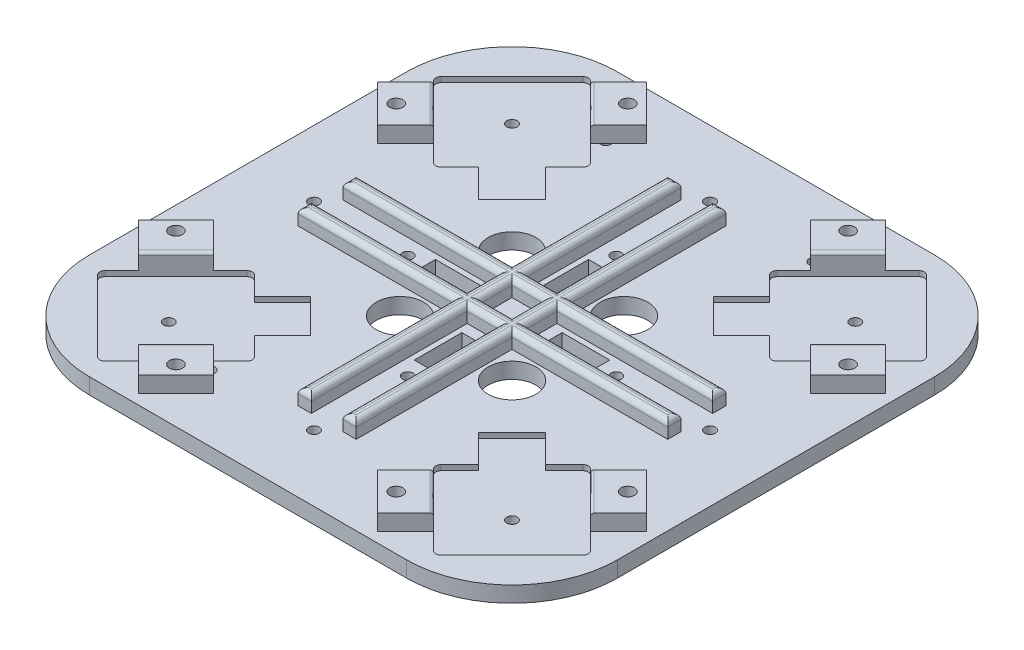
SolidWorks part; units mm, degrees
ref_plane "Спереди" through (0, 0, 0) normal (0, 0, 1) x (1, 0, 0)
ref_plane "Сверху" through (0, 0, 0) normal (0, 1, 0) x (1, 0, 0)
ref_plane "Справа" through (0, 0, 0) normal (1, 0, 0) x (0, 0, -1)
sketch "Эскиз1" plane through (0, 0, 0) normal (0, 1, 0) x (1, 0, 0)
  line L1 (-100, -100) -> (100, -100)
  line L2 (-100, -100) -> (-100, 100)
  line L3 (-100, 100) -> (100, 100)
  line L4 (100, -100) -> (100, 100)
  line L5 (0, 100) -> (0, -100) construction
  line L6 (-100, 0) -> (100, 0) construction
  line L7 (-39.5, -75) -> (39.5, -75) construction
  line L8 (-39.5, -75) -> (-39.5, 75) construction
  line L9 (-39.5, 75) -> (39.5, 75) construction
  line L10 (39.5, -75) -> (39.5, 75) construction
  line L11 (0, 75) -> (0, -75) construction
  line L12 (-39.5, 0) -> (39.5, 0) construction
  line L13 (-65, -65) -> (65, -65) construction
  line L14 (-65, -65) -> (-65, 65) construction
  line L15 (-65, 65) -> (65, 65) construction
  line L16 (65, -65) -> (65, 65) construction
  line L17 (0, 65) -> (0, -65) construction
  line L18 (-65, 0) -> (65, 0) construction
  circle A0 centre (-39.5, 75) radius 2
  circle A1 centre (39.5, 75) radius 2
  circle A2 centre (39.5, -75) radius 2
  circle A3 centre (-39.5, -75) radius 2
  circle A4 centre (39.5, 0) radius 2
  circle A5 centre (-39.5, 0) radius 2
  circle A6 centre (0, 39.5) radius 2
  circle A7 centre (0, -39.5) radius 2
  circle A8 centre (-75, 0) radius 2
  circle A9 centre (0, 75) radius 2
  circle A10 centre (75, 0) radius 2
  circle A11 centre (0, -75) radius 2
  circle A12 centre (-65, 65) radius 2
  circle A13 centre (65, 65) radius 2
  circle A14 centre (65, -65) radius 2
  circle A15 centre (-65, -65) radius 2
  point P0 (0, 0)
  point P4 (0, 0)
  point P11 (0, 0)
  point P27 (0, 0)
  dimension "D4" = 4
  dimension "D5" = 79
  dimension "D6" = 75
  dimension "D1" = 200
  dimension "D2" = 79
  dimension "D3" = 150
  dimension "D8" = 130
  dimension "D7" = 4
extrude "Бобышка-Вытянуть1" add sketch "Эскиз1" along normal blind 6
sketch "Эскиз2" plane through (0, 6, 0) normal (0, 1, 0) x (1, 0, 0)
  line L0 (0, 72.2532) -> (0, 0) construction
  line L1 (0, 0) -> (100, 100) construction
  line L2 (63.6396, 33.9411) -> (33.9411, 63.6396)
  line L3 (63.6396, 33.9411) -> (93.3381, 63.6396)
  line L4 (33.9411, 63.6396) -> (63.6396, 93.3381)
  line L5 (93.3381, 63.6396) -> (63.6396, 93.3381)
  line L6 (63.6396, 33.9411) -> (63.6396, 93.3381) construction
  line L7 (33.9411, 63.6396) -> (93.3381, 63.6396) construction
  line L8 (33.9411, -63.6396) -> (63.6396, -33.9411)
  line L9 (33.9411, -63.6396) -> (63.6396, -93.3381)
  line L10 (63.6396, -93.3381) -> (93.3381, -63.6396)
  line L11 (63.6396, -33.9411) -> (93.3381, -63.6396)
  line L12 (-63.6396, -33.9411) -> (-33.9411, -63.6396)
  line L13 (-63.6396, -33.9411) -> (-93.3381, -63.6396)
  line L14 (-93.3381, -63.6396) -> (-63.6396, -93.3381)
  line L15 (-33.9411, -63.6396) -> (-63.6396, -93.3381)
  line L16 (-33.9411, 63.6396) -> (-63.6396, 33.9411)
  line L17 (-33.9411, 63.6396) -> (-63.6396, 93.3381)
  line L18 (-63.6396, 93.3381) -> (-93.3381, 63.6396)
  line L19 (-63.6396, 33.9411) -> (-93.3381, 63.6396)
  point P6 (63.6396, 63.6396)
  point P24 (0, 0)
  dimension "D1" = 42
  dimension "D2" = 90
  dimension "D3" = 4
extrude "Вырез-Вытянуть1" cut sketch "Эскиз2" against normal blind 2
fillet "Скругление1" radius 2 16 edges at (63.6396, 5, -33.9411) (33.9411, 5, -63.6396) (93.3381, 5, -63.6396) (63.6396, 5, -93.3381) (-63.6396, 5, -93.3381) (-63.6396, 5, -33.9411) (-93.3381, 5, -63.6396) (-33.9411, 5, -63.6396) (63.6396, 5, 93.3381) (93.3381, 5, 63.6396) (63.6396, 5, 33.9411) (33.9411, 5, 63.6396) (-63.6396, 5, 93.3381) (-33.9411, 5, 63.6396) (-63.6396, 5, 33.9411) (-93.3381, 5, 63.6396)
sketch "Эскиз3" plane through (0, 6, 0) normal (0, 1, 0) x (1, 0, 0)
  line L0 (48.7904, 48.7904) -> (67.3817, 67.3817) construction
  line L1 (35.3553, 62.2254) -> (62.2254, 35.3553) construction
  line L2 (48.7904, 78.4889) -> (78.4889, 48.7904) construction
  line L3 (62.2254, 91.9239) -> (35.3553, 65.0538) construction
  line L4 (65.0538, 35.3553) -> (91.9239, 62.2254) construction
  line L5 (41.7193, 71.4178) -> (55.8614, 85.5599)
  line L6 (41.7193, 71.4178) -> (31.1127, 82.0244)
  line L7 (55.8614, 85.5599) -> (45.2548, 96.1665)
  line L8 (31.1127, 82.0244) -> (45.2548, 96.1665)
  line L9 (62.2254, 91.9239) -> (35.3553, 65.0538) construction
  line L10 (85.5599, 55.8614) -> (96.1665, 45.2548)
  line L11 (82.0244, 31.1127) -> (96.1665, 45.2548)
  line L12 (71.4178, 41.7193) -> (82.0244, 31.1127)
  line L13 (71.4178, 41.7193) -> (85.5599, 55.8614)
  line L44 (65.0538, 35.3553) -> (91.9239, 62.2254) construction
  line L45 (0, 128.3294) -> (0, 0) construction
  line L64 (0, 0) -> (145.1139, 0) construction
  line L65 (62.2254, 91.9239) -> (35.3553, 65.0538) construction
  line L90 (48.7904, -78.4889) -> (78.4889, -48.7904) construction
  line L91 (48.7904, -48.7904) -> (67.3817, -67.3817) construction
  line L92 (71.4178, -41.7193) -> (85.5599, -55.8614)
  line L93 (71.4178, -41.7193) -> (82.0244, -31.1127)
  line L94 (82.0244, -31.1127) -> (96.1665, -45.2548)
  line L95 (85.5599, -55.8614) -> (96.1665, -45.2548)
  line L96 (31.1127, -82.0244) -> (45.2548, -96.1665)
  line L97 (55.8614, -85.5599) -> (45.2548, -96.1665)
  line L98 (41.7193, -71.4178) -> (31.1127, -82.0244)
  line L99 (41.7193, -71.4178) -> (55.8614, -85.5599)
  line L100 (-48.7904, -48.7904) -> (-67.3817, -67.3817) construction
  line L101 (-48.7904, -78.4889) -> (-78.4889, -48.7904) construction
  line L102 (-48.7904, 78.4889) -> (-78.4889, 48.7904) construction
  line L103 (-48.7904, 48.7904) -> (-67.3817, 67.3817) construction
  line L104 (-41.7193, -71.4178) -> (-55.8614, -85.5599)
  line L105 (-41.7193, -71.4178) -> (-31.1127, -82.0244)
  line L106 (-55.8614, -85.5599) -> (-45.2548, -96.1665)
  line L107 (-31.1127, -82.0244) -> (-45.2548, -96.1665)
  line L108 (-85.5599, -55.8614) -> (-96.1665, -45.2548)
  line L109 (-82.0244, -31.1127) -> (-96.1665, -45.2548)
  line L110 (-71.4178, -41.7193) -> (-82.0244, -31.1127)
  line L111 (-71.4178, -41.7193) -> (-85.5599, -55.8614)
  line L112 (-71.4178, 41.7193) -> (-85.5599, 55.8614)
  line L113 (-71.4178, 41.7193) -> (-82.0244, 31.1127)
  line L114 (-82.0244, 31.1127) -> (-96.1665, 45.2548)
  line L115 (-85.5599, 55.8614) -> (-96.1665, 45.2548)
  line L116 (-31.1127, 82.0244) -> (-45.2548, 96.1665)
  line L117 (-55.8614, 85.5599) -> (-45.2548, 96.1665)
  line L118 (-41.7193, 71.4178) -> (-31.1127, 82.0244)
  line L119 (-41.7193, 71.4178) -> (-55.8614, 85.5599)
  point P16 (48.7904, 78.4889)
  dimension "D1" = 20
  dimension "D2" = 15
extrude "Бобышка-Вытянуть3" add sketch "Эскиз3" along normal blind 6
fillet "Скругление4" radius 40 4 edges at (100, 3, -100) (100, 3, 100) (-100, 3, 100) (-100, 3, -100)
sketch "Эскиз4" plane through (0, 12, 0) normal (0, 1, 0) x (1, 0, 0)
  line L0 (89.0955, 38.1838) -> (38.1838, 89.0955) construction
  line L1 (82.0244, 31.1127) -> (96.1665, 45.2548) construction
  line L2 (45.2548, 96.1665) -> (31.1127, 82.0244) construction
  line L3 (41.7193, 71.4178) -> (55.8614, 85.5599) construction
  line L4 (48.7904, 48.7904) -> (78.4889, 78.4889) construction
  line L5 (35.3553, 62.2254) -> (62.2254, 35.3553) construction
  line L6 (91.9239, 65.0538) -> (65.0538, 91.9239) construction
  line L7 (0, 119.2498) -> (0, 0) construction
  line L8 (0, 0) -> (156.895, 0) construction
  line L9 (48.7904, -48.7904) -> (78.4889, -78.4889) construction
  line L10 (89.0955, -38.1838) -> (38.1838, -89.0955) construction
  line L11 (-89.0955, -38.1838) -> (-38.1838, -89.0955) construction
  line L12 (-48.7904, -48.7904) -> (-78.4889, -78.4889) construction
  line L13 (-48.7904, 48.7904) -> (-78.4889, 78.4889) construction
  line L14 (-89.0955, 38.1838) -> (-38.1838, 89.0955) construction
  circle A0 centre (41.7193, 85.5599) radius 2.5
  circle A1 centre (85.5599, 41.7193) radius 2.5
  circle A14 centre (85.5599, -41.7193) radius 2.5
  circle A15 centre (41.7193, -85.5599) radius 2.5
  circle A16 centre (-41.7193, -85.5599) radius 2.5
  circle A17 centre (-85.5599, -41.7193) radius 2.5
  circle A18 centre (-85.5599, 41.7193) radius 2.5
  circle A19 centre (-41.7193, 85.5599) radius 2.5
  dimension "D1" = 10
  dimension "D3" = 62
extrude "Вырез-Вытянуть2" cut sketch "Эскиз4" against normal blind 8
sketch "Эскиз5" plane through (0, 6, 0) normal (0, 1, 0) x (1, 0, 0)
  line L0 (0, 85.0414) -> (0, -87.3859) construction
  line L1 (-6, 70) -> (-11, 70)
  line L2 (111.3105, 0) -> (-132.9438, 0) construction
  line L3 (6, -70) -> (11, -70)
  line L4 (6, -70) -> (6, 70)
  line L5 (6, 70) -> (11, 70)
  line L6 (11, -70) -> (11, 70)
  line L7 (8.5, 70) -> (8.5, -70) construction
  line L8 (6, 0) -> (11, 0) construction
  line L9 (-11, -70) -> (-11, 70)
  line L10 (-6, -70) -> (-11, -70)
  line L11 (-6, -70) -> (-6, 70)
  line L12 (-6, 0) -> (-11, 0) construction
  line L13 (-8.5, 70) -> (-8.5, -70) construction
  point P3 (8.5, 0)
  point P13 (-8.5, 0)
  dimension "D1" = 5
  dimension "D2" = 140
  dimension "D3" = 12
extrude "Бобышка-Вытянуть4" add sketch "Эскиз5" along normal blind 6
sketch "Эскиз6" plane through (0, 6, 0) normal (0, 1, 0) x (1, 0, 0)
  line L0 (-101.5062, 0) -> (110.1382, 0) construction
  line L1 (-70, -8.5) -> (70, -8.5) construction
  line L2 (-70, 11) -> (70, 11)
  line L3 (-70, 11) -> (-70, 6)
  line L4 (-70, 6) -> (70, 6)
  line L5 (70, 11) -> (70, 6)
  line L6 (0, 6) -> (0, 11) construction
  line L7 (-70, 8.5) -> (70, 8.5) construction
  line L8 (0, -6) -> (0, -11) construction
  line L9 (70, -11) -> (70, -6)
  line L10 (-70, -6) -> (70, -6)
  line L11 (-70, -11) -> (-70, -6)
  line L12 (-70, -11) -> (70, -11)
  point P3 (0, 8.5)
  point P15 (0, -8.5)
  dimension "D1" = 140
  dimension "D2" = 5
  dimension "D3" = 12
extrude "Бобышка-Вытянуть5" add sketch "Эскиз6" along normal blind 6
fillet "Скругление5" radius 2 32 edges at (-8.5, 12, 70) (-11, 12, -40.5) (-11, 12, 40.5) (-8.5, 12, -70) (-6, 12, -40.5) (-6, 12, 40.5) (8.5, 12, 70) (6, 12, 40.5) (6, 12, -40.5) (8.5, 12, -70) (11, 12, 40.5) (11, 12, -40.5) (0, 12, -6) (-6, 12, 0) (0, 12, 6) (6, 12, 0) (-40.5, 12, 11) (-70, 12, 8.5) (-40.5, 12, 6) (-11, 12, 0) (-40.5, 12, -6) (-70, 12, -8.5) (-40.5, 12, -11) (0, 12, -11) (40.5, 12, -11) (70, 12, -8.5) (40.5, 12, -6) (11, 12, 0) (40.5, 12, 6) (70, 12, 8.5) (40.5, 12, 11) (0, 12, 11)
sketch "Эскиз7" plane through (0, 6, 0) normal (0, 1, 0) x (1, 0, 0)
  line L0 (0, 76.3028) -> (0, 0) construction
  line L1 (0, 0) -> (74.3797, 74.3797) construction
  line L2 (15, 4) -> (33, 4)
  line L3 (-4, 15) -> (4, 15)
  line L4 (-4, 15) -> (-4, 33)
  line L5 (-4, 33) -> (4, 33)
  line L6 (4, 15) -> (4, 33)
  line L7 (0, 33) -> (0, 15) construction
  line L8 (-4, 24) -> (4, 24) construction
  line L9 (15, 4) -> (15, -4)
  line L10 (15, -4) -> (33, -4)
  line L11 (33, 4) -> (33, -4)
  line L12 (4, -15) -> (4, -33)
  line L13 (4, -15) -> (-4, -15)
  line L14 (-4, -15) -> (-4, -33)
  line L15 (4, -33) -> (-4, -33)
  line L16 (-15, -4) -> (-33, -4)
  line L17 (-15, -4) -> (-15, 4)
  line L18 (-15, 4) -> (-33, 4)
  line L19 (-33, -4) -> (-33, 4)
  circle A0 centre (21.2132, 21.2132) radius 9
  circle A1 centre (21.2132, -21.2132) radius 9
  circle A2 centre (-21.2132, -21.2132) radius 9
  circle A3 centre (-21.2132, 21.2132) radius 9
  point P6 (0, 24)
  point P15 (0, 0)
  point P32 (0, 0)
  dimension "D1" = 30
  dimension "D2" = 18
  dimension "D4" = 8
  dimension "D5" = 18
  dimension "D6" = 24
  dimension "D3" = 4
  dimension "D7" = 4
extrude "Вырез-Вытянуть3" cut sketch "Эскиз7" against normal blind 6
sketch "Эскиз8" plane through (0, 6, 0) normal (0, 1, 0) x (1, 0, 0)
  line L0 (48.7904, 48.7904) -> (72.3205, 72.3205) construction
  line L1 (35.3553, 62.2254) -> (62.2254, 35.3553) construction
  line L2 (44.5477, 31.8198) -> (31.8198, 44.5477)
  line L3 (44.5477, 31.8198) -> (65.7609, 53.033)
  line L4 (31.8198, 44.5477) -> (53.033, 65.7609)
  line L5 (65.7609, 53.033) -> (53.033, 65.7609)
  line L6 (44.5477, 31.8198) -> (53.033, 65.7609) construction
  line L7 (31.8198, 44.5477) -> (65.7609, 53.033) construction
  line L20 (0, 107.5006) -> (0, 0) construction
  line L21 (0, 0) -> (140.6034, 0) construction
  line L22 (31.8198, -44.5477) -> (65.7609, -53.033) construction
  line L23 (44.5477, -31.8198) -> (53.033, -65.7609) construction
  line L24 (48.7904, -48.7904) -> (72.3205, -72.3205) construction
  line L25 (65.7609, -53.033) -> (53.033, -65.7609)
  line L26 (31.8198, -44.5477) -> (53.033, -65.7609)
  line L27 (44.5477, -31.8198) -> (65.7609, -53.033)
  line L28 (44.5477, -31.8198) -> (31.8198, -44.5477)
  line L29 (-48.7904, -48.7904) -> (-72.3205, -72.3205) construction
  line L30 (-44.5477, -31.8198) -> (-53.033, -65.7609) construction
  line L31 (-31.8198, -44.5477) -> (-65.7609, -53.033) construction
  line L32 (-31.8198, 44.5477) -> (-65.7609, 53.033) construction
  line L33 (-44.5477, 31.8198) -> (-53.033, 65.7609) construction
  line L34 (-48.7904, 48.7904) -> (-72.3205, 72.3205) construction
  line L35 (-44.5477, -31.8198) -> (-31.8198, -44.5477)
  line L36 (-44.5477, -31.8198) -> (-65.7609, -53.033)
  line L37 (-31.8198, -44.5477) -> (-53.033, -65.7609)
  line L38 (-65.7609, -53.033) -> (-53.033, -65.7609)
  line L39 (-65.7609, 53.033) -> (-53.033, 65.7609)
  line L40 (-31.8198, 44.5477) -> (-53.033, 65.7609)
  line L41 (-44.5477, 31.8198) -> (-65.7609, 53.033)
  line L42 (-44.5477, 31.8198) -> (-31.8198, 44.5477)
  point P24 (0, 16.9706)
  dimension "D1" = 18
  dimension "D2" = 30
extrude "Вырез-Вытянуть4" cut sketch "Эскиз8" against normal blind 2 contours L2 L3 L5 L4
fillet "Скругление6" radius 1 8 edges at (78.4889, 12, -48.7904) (48.7904, 12, -78.4889) (-78.4889, 12, 48.7904) (-48.7904, 12, 78.4889) (48.7904, 12, 78.4889) (78.4889, 12, 48.7904) (-78.4889, 12, -48.7904) (-48.7904, 12, -78.4889)
